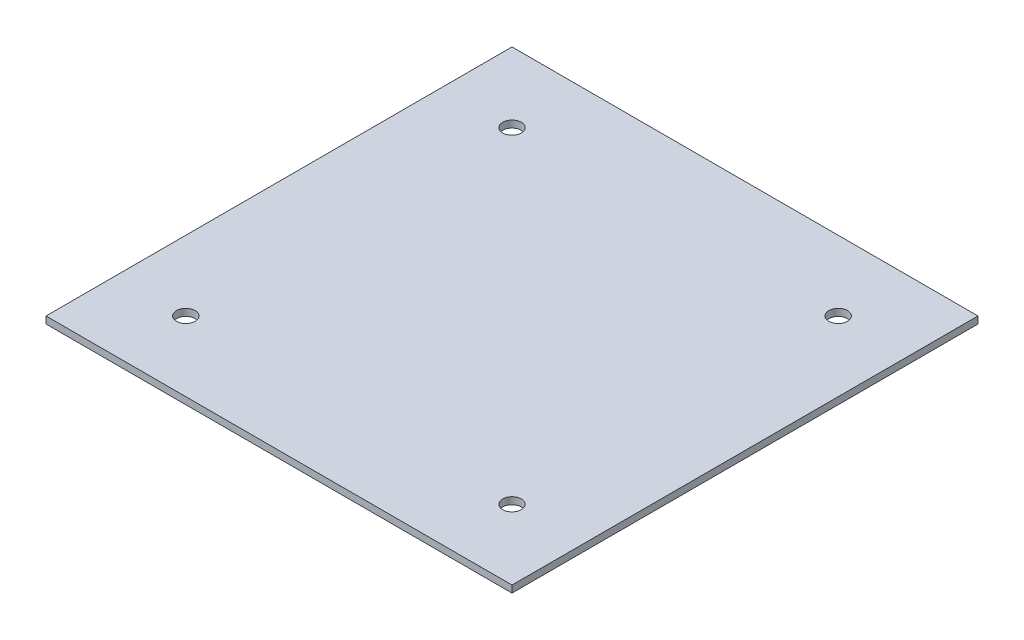
SolidWorks part; units mm, degrees
ref_plane "Přední rovina" through (0, 0, 0) normal (0, 0, 1) x (1, 0, 0)
ref_plane "Horní rovina" through (0, 0, 0) normal (0, 1, 0) x (1, 0, 0)
ref_plane "Pravá rovina" through (0, 0, 0) normal (1, 0, 0) x (0, 0, -1)
sketch "Skica1" plane through (0, 0, 0) normal (0, 1, 0) x (1, 0, 0)
  line L1 (0, 0) -> (200, 0)
  line L2 (0, 0) -> (0, 200)
  line L3 (0, 200) -> (200, 200)
  line L4 (200, 0) -> (200, 200)
  circle A0 centre (30, 170) radius 4
  circle A1 centre (170, 170) radius 4
  circle A2 centre (170, 30) radius 4
  circle A3 centre (30, 30) radius 4
  dimension "D3" = 8
  dimension "D1" = 200
  dimension "D2" = 200
  dimension "D4" = 30
  dimension "D5" = 30
  dimension "D8" = 140
  dimension "D9" = 140
  dimension "D6" = 2
  dimension "D7" = 2
extrude "Přidat vysunutím1" add sketch "Skica1" along normal blind 3
